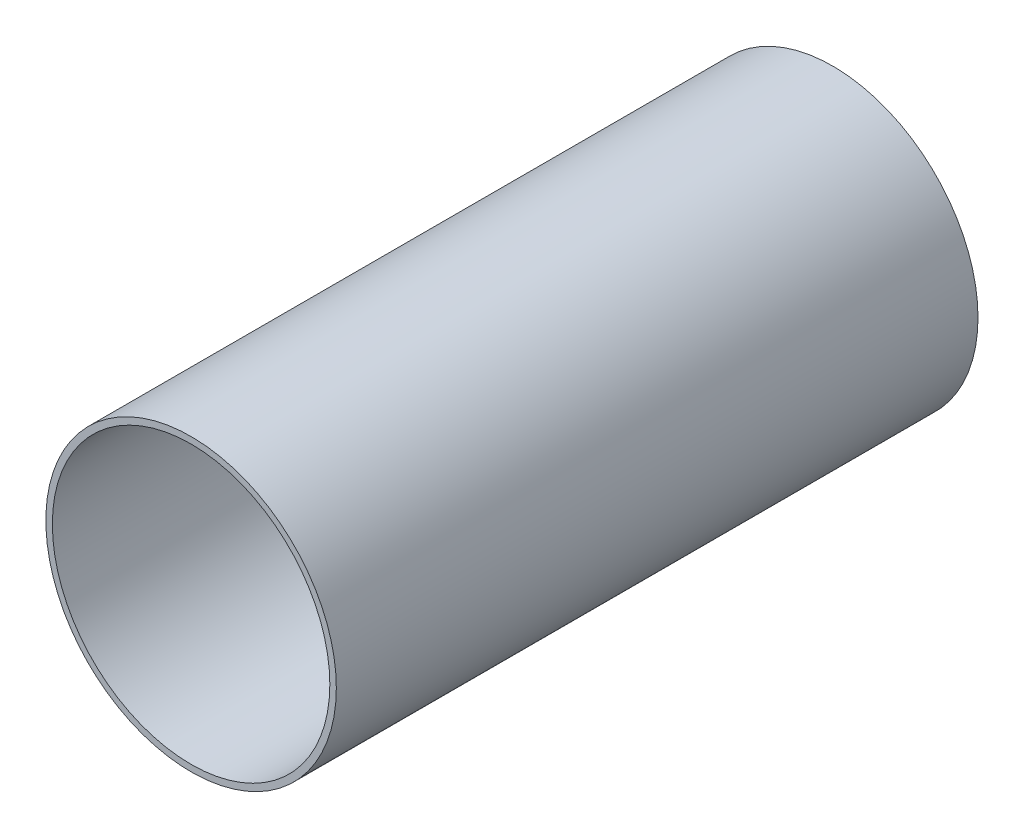
SolidWorks part; units mm, degrees
material "6061 Alloy"
ref_plane "Front Plane" through (0, 0, 0) normal (0, 0, 1) x (1, 0, 0)
ref_plane "Top Plane" through (0, 0, 0) normal (0, 1, 0) x (1, 0, 0)
ref_plane "Right Plane" through (0, 0, 0) normal (1, 0, 0) x (0, 0, -1)
sketch "Sketch1" plane through (0, 0, 0) normal (0, 0, 1) x (1, 0, 0)
  circle A0 centre (0, 0) radius 53.1812
  circle A1 centre (0, 0) radius 50.8
  dimension "D1" = 101.6
  dimension "D2" = 106.3625
extrude "Boss-Extrude1" add sketch "Sketch1" along normal blind 234.95
